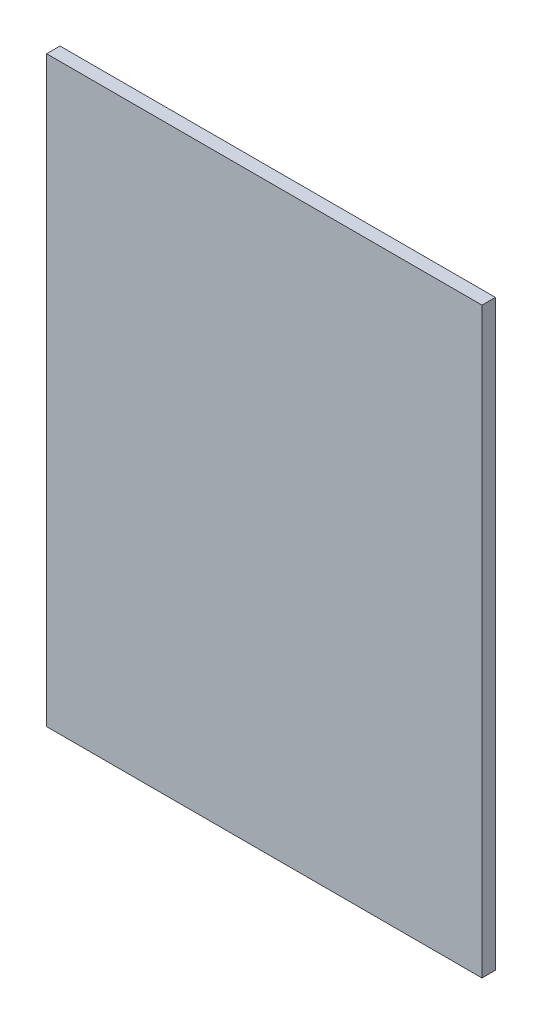
SolidWorks part; units mm, degrees
ref_plane "Спереди" through (0, 0, 0) normal (0, 0, 1) x (1, 0, 0)
ref_plane "Сверху" through (0, 0, 0) normal (0, 1, 0) x (1, 0, 0)
ref_plane "Справа" through (0, 0, 0) normal (1, 0, 0) x (0, 0, -1)
sketch "Эскиз1" plane through (0, 0, 0) normal (0, 0, 1) x (1, 0, 0)
  line L1 (-32.5, 43.5) -> (32.5, 43.5)
  line L2 (-32.5, 43.5) -> (-32.5, -43.5)
  line L3 (-32.5, -43.5) -> (32.5, -43.5)
  line L4 (32.5, 43.5) -> (32.5, -43.5)
  line L5 (-32.5, 43.5) -> (32.5, -43.5) construction
  line L6 (-32.5, -43.5) -> (32.5, 43.5) construction
  point P0 (0, 0)
  dimension "D1" = 65
  dimension "D2" = 87
extrude "Бобышка-Вытянуть1" add sketch "Эскиз1" along normal blind 2
